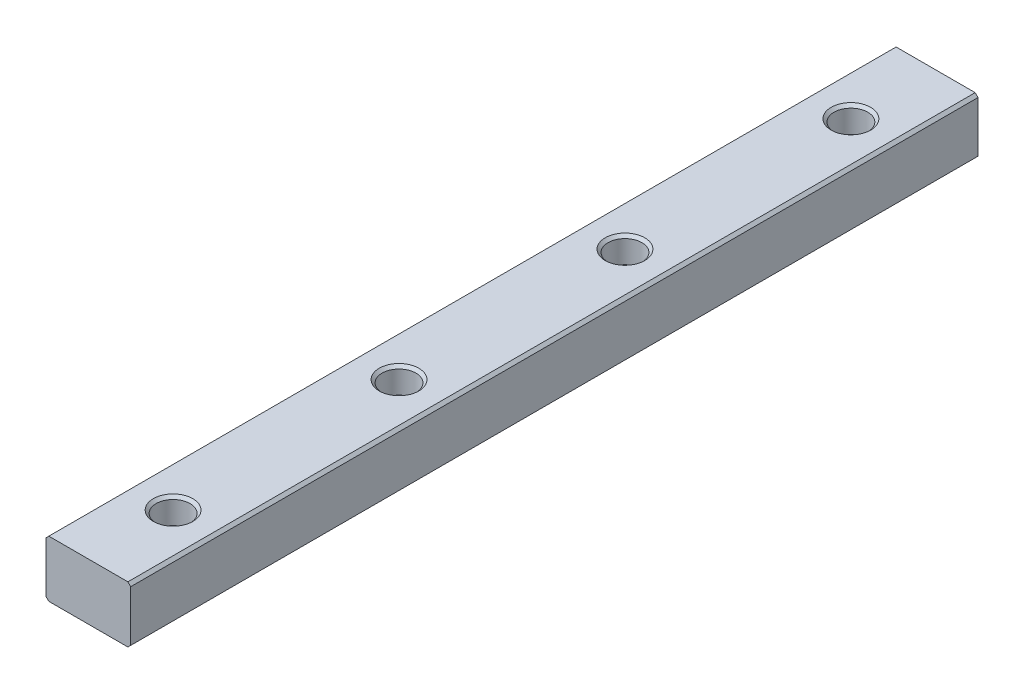
SolidWorks part; units mm, degrees
ref_plane "Front Plane" through (0, 0, 0) normal (0, 0, 1) x (1, 0, 0)
ref_plane "Top Plane" through (0, 0, 0) normal (0, 1, 0) x (1, 0, 0)
ref_plane "Right Plane" through (0, 0, 0) normal (1, 0, 0) x (0, 0, -1)
sketch "Sketch1" plane through (0, 0, 0) normal (0, 0, 1) x (1, 0, 0)
  line L1 (7.5, -5) -> (-7.5, -5)
  line L2 (7.5, -5) -> (7.5, 5)
  line L3 (7.5, 5) -> (-7.5, 5)
  line L4 (-7.5, -5) -> (-7.5, 5)
  line L5 (7.5, -5) -> (-7.5, 5) construction
  line L6 (7.5, 5) -> (-7.5, -5) construction
  point P0 (0, 0)
  dimension "D1" = 15
  dimension "D2" = 10
extrude "Boss-Extrude1" add sketch "Sketch1" along normal mid plane 150
sketch "Sketch2" plane through (0, 5, 0) normal (0, 1, 0) x (1, 0, 0)
  line L0 (0, -1000) -> (0, 49000) construction
  line L1 (-1000, -60) -> (49000, -60) construction
  line L2 (7.5, -75) -> (-7.5, -75) construction
  circle A0 centre (0, -60) radius 3
  dimension "D2" = 6
  dimension "D1" = 15
extrude "Cut-Extrude1" cut sketch "Sketch2" against normal blind 4.5
sketch "Sketch3" plane through (0, 0.5, 0) normal (0, 1, 0) x (1, 0, 0)
  circle A0 centre (0, -60) radius 1.75
  dimension "D1" = 3.5
extrude "Cut-Extrude2" cut sketch "Sketch3" against normal through all
chamfer "Chamfer1" distance 0.5 angle 45 2 edges at (-3, 5, 60) (-1.75, -5, 60)
pattern_linear "LPattern1" count 4 spacing 40 along (0, 0, -1) of "Cut-Extrude1", "Cut-Extrude2", "Chamfer1"
chamfer "Chamfer2" distance 0.5 angle 45 4 edges at (-7.5, -5, 0) (7.5, -5, 0) (7.5, 5, 0) (-7.5, 5, 0)
